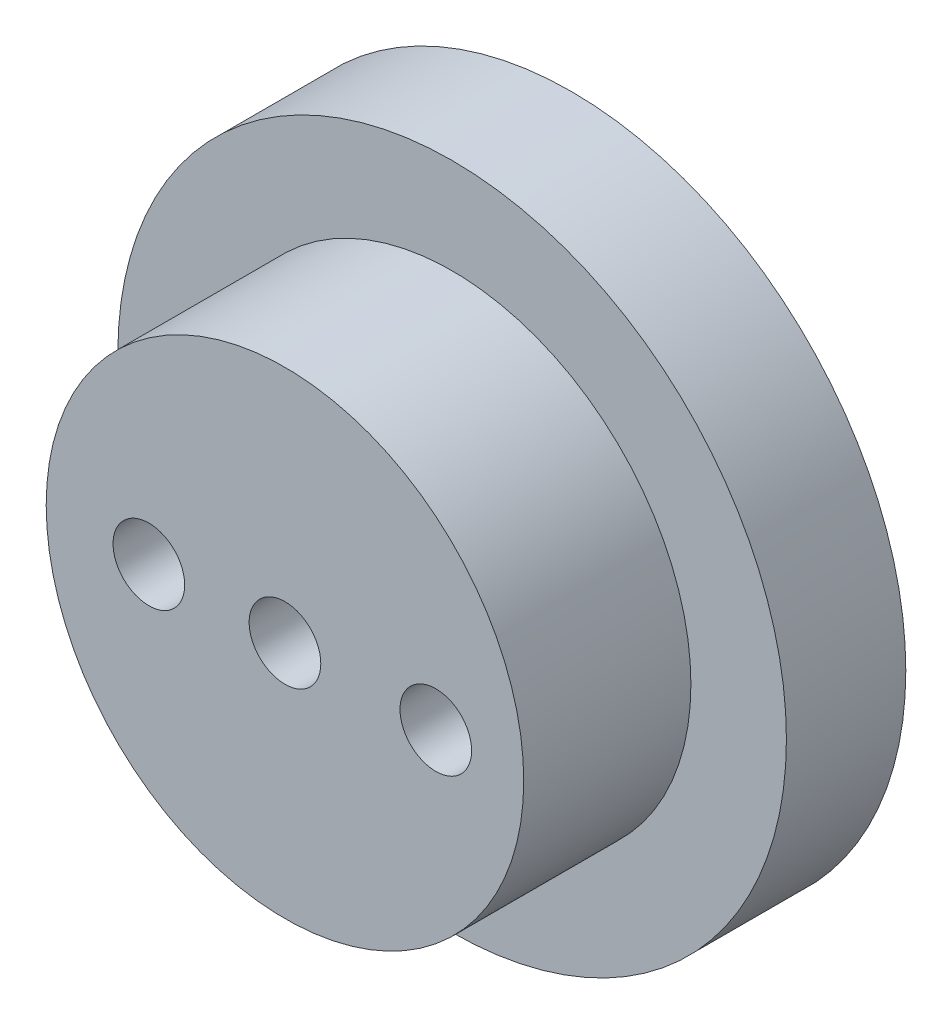
SolidWorks part; units mm, degrees
ref_plane "Front Plane" through (0, 0, 0) normal (0, 0, 1) x (1, 0, 0)
ref_plane "Top Plane" through (0, 0, 0) normal (0, 1, 0) x (1, 0, 0)
ref_plane "Right Plane" through (0, 0, 0) normal (1, 0, 0) x (0, 0, -1)
sketch "Sketch1" plane through (0, 0, 0) normal (0, 0, 1) x (1, 0, 0)
  circle A0 centre (0, 0) radius 14
  dimension "D1" = 28
extrude "Boss-Extrude1" add sketch "Sketch1" along normal blind 5
sketch "Sketch2" plane through (0, 0, 5) normal (0, 0, 1) x (1, 0, 0)
  circle A0 centre (0, 0) radius 10
  dimension "D1" = 20
extrude "Boss-Extrude2" add sketch "Sketch2" along normal blind 7
sketch "Sketch3" plane through (0, 0, 12) normal (0, 0, 1) x (1, 0, 0)
  circle A0 centre (0, 0) radius 1.5
  dimension "D1" = 3
extrude "Cut-Extrude1" cut sketch "Sketch3" against normal through all
sketch "Sketch4" plane through (0, 0, 12) normal (0, 0, 1) x (1, 0, 0)
  line L1 (-2.8, 6.1) -> (2.8, 6.1)
  line L2 (-2.8, 6.1) -> (-2.8, 3.5)
  line L3 (-2.8, 3.5) -> (2.8, 3.5)
  line L4 (2.8, 6.1) -> (2.8, 3.5)
  line L5 (-2.8, 6.1) -> (2.8, 3.5) construction
  line L6 (-2.8, 3.5) -> (2.8, 6.1) construction
  line L7 (-2.8, -3.5) -> (2.8, -3.5)
  line L8 (-2.8, -3.5) -> (-2.8, -6.1)
  line L9 (-2.8, -6.1) -> (2.8, -6.1)
  line L10 (2.8, -3.5) -> (2.8, -6.1)
  line L11 (-2.8, -3.5) -> (2.8, -6.1) construction
  line L12 (-2.8, -6.1) -> (2.8, -3.5) construction
  circle A0 centre (0, 0) radius 1.5 construction
  circle A1 centre (-5.6997, 0) radius 1.5
  circle A2 centre (6.317, 0) radius 1.5
  point P0 (0, 4.8)
  point P5 (0, -4.8)
  dimension "D1" = 3.5
  dimension "D7" = 3
  dimension "D8" = 3
  dimension "D2" = 3.5
  dimension "D3" = 5.6
  dimension "D4" = 2.6
  dimension "D5" = 2.6
  dimension "D6" = 5.6
extrude "Cut-Extrude2" cut sketch "Sketch4" against normal up to next contours A1 | A2
